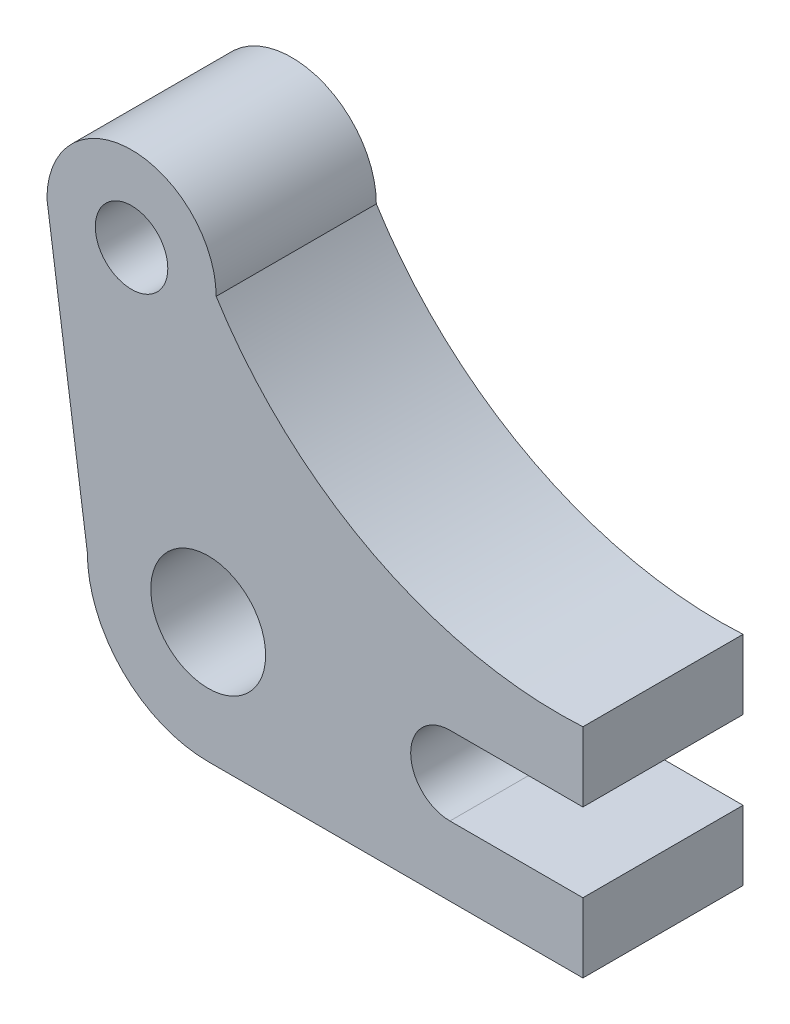
SolidWorks part; units mm, degrees
material "AISI 1020 Steel, Cold Rolled"
ref_plane "Front Plane" through (0, 0, 0) normal (0, 0, 1) x (1, 0, 0)
ref_plane "Top Plane" through (0, 0, 0) normal (0, 1, 0) x (1, 0, 0)
ref_plane "Right Plane" through (0, 0, 0) normal (1, 0, 0) x (0, 0, -1)
sketch "Sketch1" plane through (0, 0, 0) normal (0, 0, 1) x (1, 0, 0)
  line L0 (0, 0) -> (-12.6821, 47.3304) construction
  line L1 (-26.6821, 47.3304) -> (-20, 0)
  line L2 (0, -20) -> (62, -20)
  line L3 (62, -20) -> (62, -2)
  line L4 (40, -2) -> (62, -2) construction
  line L5 (40, 4.5) -> (62, 4.5)
  line L6 (40, -8.5) -> (62, -8.5)
  line L7 (62, 4.5) -> (62, 16)
  circle A0 centre (0, 0) radius 9.5
  circle A1 centre (-12.6821, 47.3304) radius 6
  circle A2 centre (0, 0) radius 20
  circle A3 centre (-12.6821, 47.3304) radius 14
  arc A4 (40, 4.5) -> (40, -8.5) centre (40, -2) ccw
  arc A5 (62, -8.5) -> (62, 4.5) centre (62, -2) ccw
  arc A7 (1.3179, 47.3304) -> (62, 16) centre (58.1047, 82.8867) ccw
  point P14 (51, -2)
  point P19 (0, 0)
  point P24 (0, 0)
  point P25 (0, 0)
  dimension "D1" = 19
  dimension "D2" = 12
  dimension "D4" = 40
  dimension "D5" = 28
  dimension "D8" = 6.5
  dimension "D11" = 67
  dimension "D3" = 15
  dimension "D6" = 62
  dimension "D7" = 22
  dimension "D9" = 36
  dimension "D10" = 49
  dimension "D12" = 13
  dimension "D13" = 18
  dimension "D14" = 18
extrude "Boss-Extrude1" add sketch "Sketch1" along normal blind 26.5 contours A7 A3 L1 A2 L2 L3 L6 A4 L5 L7 | L1 A3 A1 | A2 A0
equation "\"a\"= 62mm"
equation "\"b\" = 20mm"
equation "\"c\"= 26.5mm"
